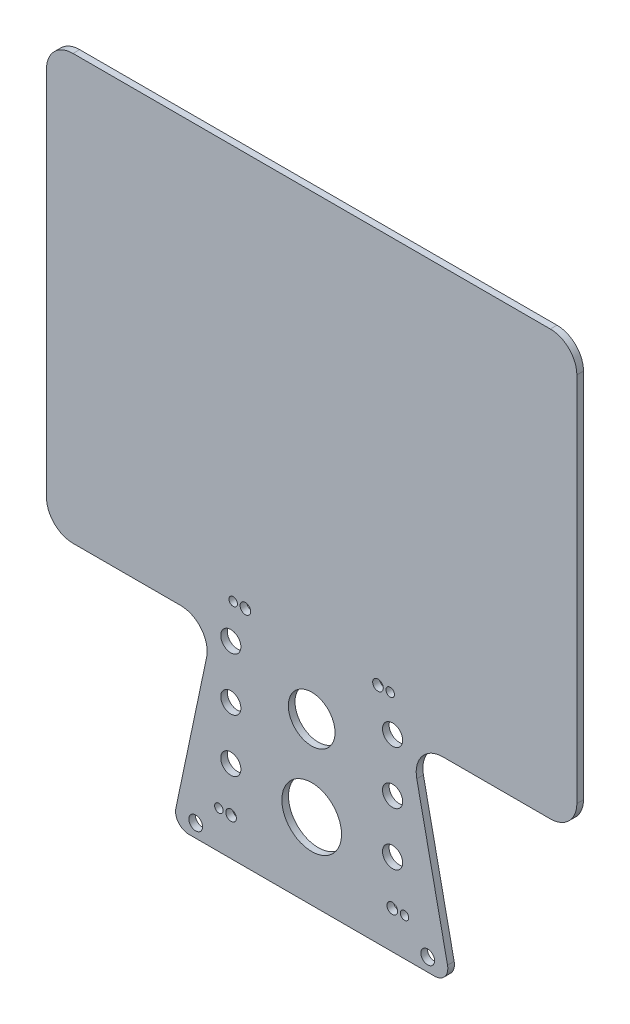
SolidWorks part; units mm, degrees
material "6061-T6 (SS)"
ref_plane "Front Plane" through (0, 0, 0) normal (0, 0, 1) x (1, 0, 0)
ref_plane "Top Plane" through (0, 0, 0) normal (0, 1, 0) x (1, 0, 0)
ref_plane "Right Plane" through (0, 0, 0) normal (1, 0, 0) x (0, 0, -1)
sketch "Sketch1" plane through (0, 0, 0) normal (0, 0, 1) x (1, 0, 0)
  line L0 (0, 0) -> (-82.55, 0)
  line L1 (-82.55, 0) -> (-107.95, -120.65)
  line L2 (-107.95, -120.65) -> (25.4, -120.65)
  line L3 (25.4, -120.65) -> (0, 0)
  dimension "D1" = 82.55
  dimension "D2" = 133.35
  dimension "D3" = 120.65
extrude "Boss-Extrude1" add sketch "Sketch1" along normal blind 3.175
fillet "Fillet1" radius 6.35 4 edges at (25.4, -120.65, 1.5875) (-107.95, -120.65, 1.5875) (-82.55, 0, 1.5875) (0, 0, 1.5875)
sketch "Sketch2" plane through (0, 0, 0) normal (0, 0, -1) x (-1, 0, 0)
  line L0 (-10.9855, -114.3) -> (93.5355, -114.3) construction
  line L1 (41.275, -114.3) -> (41.275, -120.65) construction
  line L2 (100.124, -120.65) -> (-17.574, -120.65) construction
  circle A0 centre (-14.2875, -114.3) radius 3.302
  circle A1 centre (96.8375, -114.3) radius 3.302
  dimension "D2" = 6.604
  dimension "D1" = 104.521
  dimension "D3" = 6.35
extrude "Cut-Extrude1" cut sketch "Sketch2" against normal through all
sketch "Sketch3" plane through (0, 0, 0) normal (0, 0, -1) x (-1, 0, 0)
  line L0 (12.065, -13.462) -> (70.485, -13.462) construction
  line L3 (41.275, -13.462) -> (41.275, 0) construction
  line L4 (5.1524, 0) -> (77.3976, 0) construction
  line L5 (5.715, -13.462) -> (76.835, -13.462) construction
  circle A0 centre (9.525, -13.462) radius 2.54
  circle A1 centre (73.025, -13.462) radius 2.54
  circle A2 centre (-14.2875, -114.3) radius 3.302 construction
  circle A3 centre (3.683, -13.462) radius 2.032
  circle A4 centre (78.867, -13.462) radius 2.032
  point P21 (41.275, -13.462)
  dimension "D2" = 5.08
  dimension "D5" = 4.064
  dimension "D3" = 100.838
  dimension "D1" = 58.42
  dimension "D4" = 71.12
extrude "Cut-Extrude2" cut sketch "Sketch3" against normal through all
sketch "Sketch4" plane through (0, 0, 3.175) normal (0, 0, 1) x (1, 0, 0)
  line L1 (-41.275, 0) -> (-41.275, -84.074) construction
  line L2 (-5.1524, 0) -> (-77.3976, 0) construction
  line L3 (-85.725, -102.616) -> (3.175, -102.616) construction
  line L4 (-41.275, -102.616) -> (-41.275, -84.074) construction
  circle A0 centre (-41.275, -84.074) radius 14.2875
  circle A1 centre (-41.275, -43.434) radius 11.176
  circle A2 centre (14.2875, -114.3) radius 3.302 construction
  circle A3 centre (-2.667, -102.616) radius 2.54
  circle A4 centre (-79.883, -102.616) radius 2.54
  circle A5 centre (-85.725, -102.616) radius 2.032
  circle A6 centre (3.175, -102.616) radius 2.032
  circle A7 centre (-9.525, -13.462) radius 2.54 construction
  circle A8 centre (-78.867, -13.462) radius 2.032 construction
  dimension "D1" = 28.575
  dimension "D3" = 22.352
  dimension "D5" = 5.842
  dimension "D6" = 5.842
  dimension "D8" = 77.216
  dimension "D2" = 30.226
  dimension "D4" = 40.64
  dimension "D7" = 89.154
extrude "Cut-Extrude3" cut sketch "Sketch4" against normal through all
sketch "Sketch5" plane through (0, 0, 3.175) normal (0, 0, 1) x (1, 0, 0)
  line L0 (-80.01, -30.48) -> (-80.01, -81.28) construction
  line L1 (-2.54, -30.48) -> (-2.54, -81.28) construction
  line L2 (-80.01, -30.48) -> (-2.54, -30.48) construction
  line L3 (-41.275, -30.48) -> (-41.275, 0) construction
  line L4 (-5.1524, 0) -> (-77.3976, 0) construction
  circle A0 centre (-80.01, -30.48) radius 4.826
  circle A1 centre (-80.01, -55.88) radius 4.826
  circle A2 centre (-80.01, -81.28) radius 4.826
  circle A3 centre (-2.54, -81.28) radius 4.826
  circle A4 centre (-2.54, -55.88) radius 4.826
  circle A5 centre (-2.54, -30.48) radius 4.826
  circle A6 centre (-73.025, -13.462) radius 2.54 construction
  dimension "D2" = 9.652
  dimension "D4" = 25.4
  dimension "D5" = 77.47
  dimension "D1" = 17.018
  dimension "D3" = 50.8
extrude "Cut-Extrude4" cut sketch "Sketch5" against normal through all
sketch "Sketch6" plane through (0, 0, 3.175) normal (0, 0, 1) x (1, 0, 0)
  line L0 (-88.3786, -27.686) -> (-168.275, -27.686)
  line L1 (-83.6114, -5.0418) -> (-106.3378, -112.9918) construction
  line L2 (-5.1524, 0) -> (-77.3976, 0) construction
  line L3 (5.8286, -27.686) -> (85.725, -27.686)
  line L4 (23.7878, -112.9918) -> (1.0614, -5.0418) construction
  line L5 (-168.275, -27.686) -> (-168.275, 175.514)
  line L6 (-168.275, 175.514) -> (85.725, 175.514)
  line L7 (85.725, 175.514) -> (85.725, -27.686)
  line L8 (-83.6114, -5.0418) -> (-88.3786, -27.686)
  line L9 (-5.1524, 0) -> (-77.3976, 0)
  line L10 (5.8286, -27.686) -> (1.0614, -5.0418)
  line L11 (-41.275, 175.514) -> (-41.275, 0) construction
  arc A0 (-77.3976, 0) -> (-83.6114, -5.0418) centre (-77.3976, -6.35) ccw construction
  arc A1 (1.0614, -5.0418) -> (-5.1524, 0) centre (-5.1524, -6.35) ccw construction
  arc A2 (-77.3976, 0) -> (-83.6114, -5.0418) centre (-77.3976, -6.35) ccw
  arc A3 (1.0614, -5.0418) -> (-5.1524, 0) centre (-5.1524, -6.35) ccw
  dimension "D1" = 27.686
  dimension "D2" = 203.2
  dimension "D3" = 254
extrude "Boss-Extrude2" add sketch "Sketch6" against normal up to surface (3.175 mm away) up to face at (2.286, -30.48, 0)
fillet "Fillet2" radius 12.7 2 edges at (5.8286, -27.686, 1.5875) (-88.3786, -27.686, 1.5875)
fillet "Fillet3" radius 12.7 4 edges at (-168.275, 175.514, 1.5875) (85.725, 175.514, 1.5875) (85.725, -27.686, 1.5875) (-168.275, -27.686, 1.5875)
